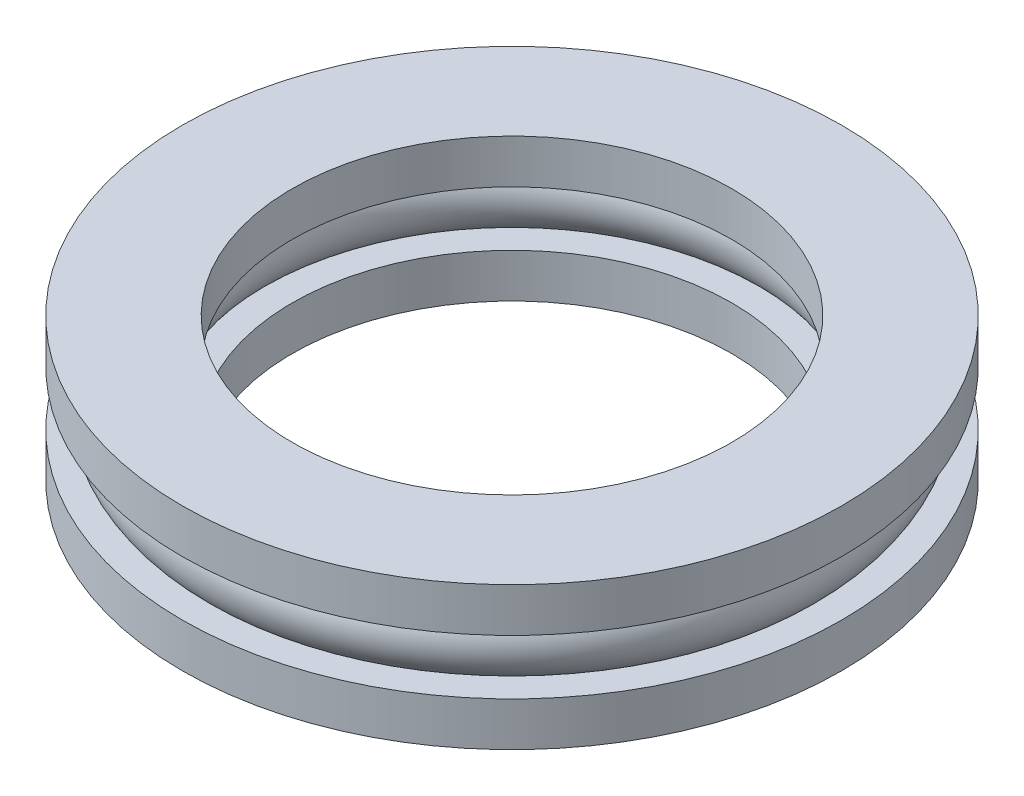
SolidWorks part; units mm, degrees
ref_plane "Front Plane" through (0, 0, 0) normal (0, 0, 1) x (1, 0, 0)
ref_plane "Top Plane" through (0, 0, 0) normal (0, 1, 0) x (1, 0, 0)
ref_plane "Right Plane" through (0, 0, 0) normal (1, 0, 0) x (0, 0, -1)
sketch "Sketch1" plane through (0, 0, 0) normal (0, 0, 1) x (1, 0, 0)
  line L0 (20, 2.5) -> (30, 2.5)
  line L1 (20, 6.5) -> (30, 6.5)
  line L2 (20, 6.5) -> (20, -6.5)
  line L3 (20, -6.5) -> (30, -6.5)
  line L4 (30, 6.5) -> (30, -6.5)
  line L5 (20, 6.5) -> (30, -6.5) construction
  line L6 (20, -6.5) -> (30, 6.5) construction
  line L7 (20, -2.5) -> (30, -2.5)
  line L8 (0, 0) -> (0, 7.8694) construction
  circle A0 centre (25, 0) radius 3.5
  dimension "D1" = 25
  dimension "D4" = 7
  dimension "D2" = 13
  dimension "D3" = 10
  dimension "D5" = 4
  dimension "D6" = 4
revolve "Revolve1" add sketch "Sketch1" angle 360 about L8
